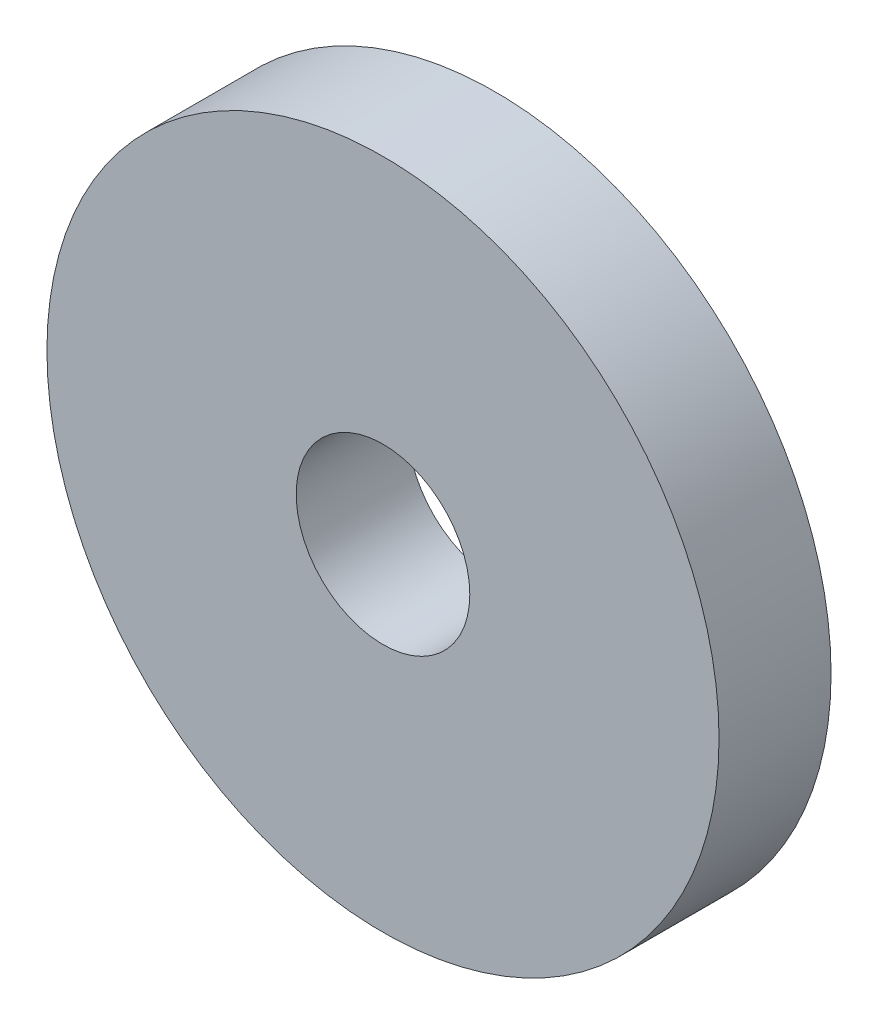
SolidWorks part; units mm, degrees
material "Thornel Mat VMA"
ref_plane "前视基准面" through (0, 0, 0) normal (0, 0, 1) x (1, 0, 0)
ref_plane "上视基准面" through (0, 0, 0) normal (0, 1, 0) x (1, 0, 0)
ref_plane "右视基准面" through (0, 0, 0) normal (1, 0, 0) x (0, 0, -1)
sketch "草图1" plane through (0, 0, 0) normal (0, 0, 1) x (1, 0, 0)
  circle A0 centre (0, 0) radius 4 construction
  circle A1 centre (0, 0) radius 6
  circle A2 centre (0, 0) radius 1.55
  dimension "D1" = 8
  dimension "D2" = 2
  dimension "D3" = 3.1
extrude "凸台-拉伸1" add sketch "草图1" along normal blind 2
